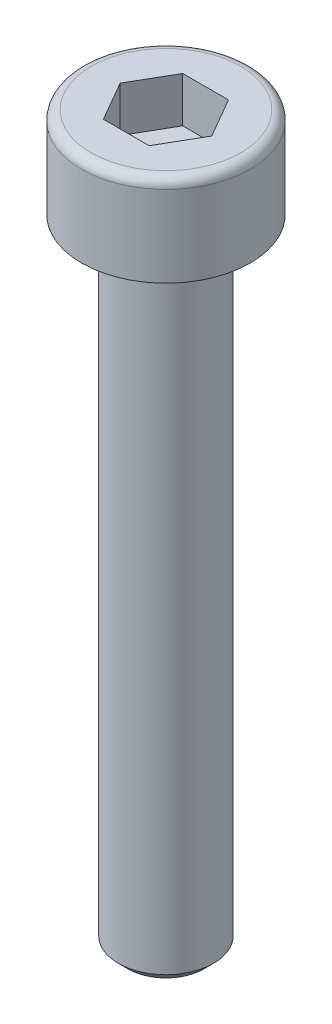
SolidWorks part; units mm, degrees
material "Cast Stainless Steel"
ref_plane "Front Plane" through (0, 0, 0) normal (0, 0, 1) x (1, 0, 0)
ref_plane "Top Plane" through (0, 0, 0) normal (0, 1, 0) x (1, 0, 0)
ref_plane "Right Plane" through (0, 0, 0) normal (1, 0, 0) x (0, 0, -1)
sketch "Sketch1" plane through (0, 0, 0) normal (0, 0, 1) x (1, 0, 0)
  line L0 (0, 0) -> (0, 2.86)
  line L1 (0, 2.86) -> (2.66, 2.86)
  line L2 (2.66, 2.86) -> (2.66, 0)
  line L3 (2.66, 0) -> (1.5, 0)
  line L4 (1.5, 0) -> (1.5, -20)
  line L5 (1.5, -20) -> (0, -20)
  line L6 (0, -20) -> (0, 0)
  line L7 (0, 2.86) -> (0, 12.7536) construction
  dimension "D1" = 20
  dimension "D2" = 2.86
  dimension "D3" = 3
  dimension "D4" = 5.32
revolve "Revolve1" add sketch "Sketch1" angle 360 about L7
chamfer "Chamfer1" distance 0.3 angle 45 1 edges at (0, -20, -1.5)
fillet "Fillet1" radius 0.3 1 edges at (0, 2.86, -2.66)
sketch "Sketch2" plane through (0, 2.86, 0) normal (0, 1, 0) x (1, 0, 0)
  line L1 (0.7217, -1.25) -> (1.4434, 0)
  line L2 (1.4434, 0) -> (0.7217, 1.25)
  line L3 (0.7217, 1.25) -> (-0.7217, 1.25)
  line L4 (-0.7217, 1.25) -> (-1.4434, 0)
  line L5 (-1.4434, 0) -> (-0.7217, -1.25)
  line L6 (-0.7217, -1.25) -> (0.7217, -1.25)
  circle A0 centre (0, 0) radius 1.25 construction
  dimension "D1" = 2.5
extrude "Cut-Extrude1" cut sketch "Sketch2" against normal blind 1.43
equation "\"d\"= 3"
equation "\"dk\"= 5.32"
equation "\"k\"= 2.86"
equation "\"s\"= 2.5"
equation "\"L\" = 20"
equation "\"D4@Sketch1\"=\"dk\""
equation "\"D2@Sketch1\"=\"k\""
equation "\"D1@Sketch1\"=\"L\""
equation "\"D3@Sketch1\"=\"d\""
equation "\"D1@Chamfer1\"=\"d\"/10"
equation "\"D1@Fillet1\"=\"d\"/10"
equation "\"D1@Sketch2\"=\"s\""
equation "\"D1@Cut-Extrude1\"=\"k\"/2"
